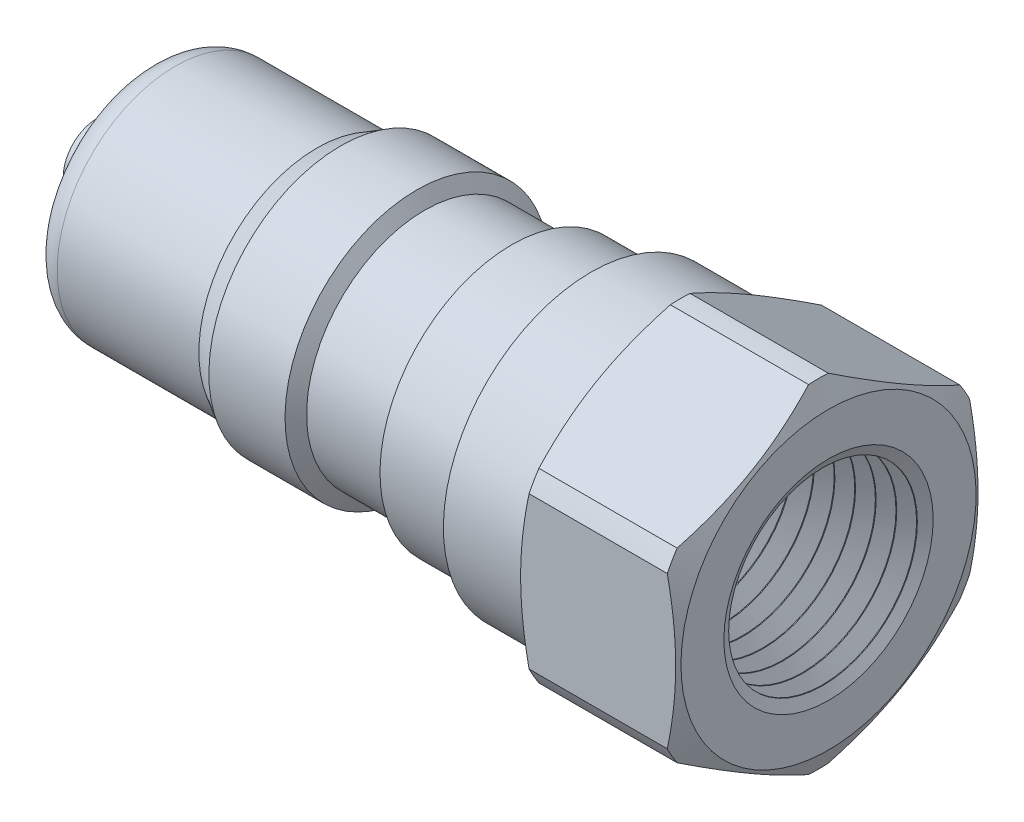
SolidWorks part; units mm, degrees
ref_plane "Front" through (0, 0, 0) normal (0, 0, 1) x (1, 0, 0)
ref_plane "Top" through (0, 0, 0) normal (0, 1, 0) x (1, 0, 0)
ref_plane "Right" through (0, 0, 0) normal (1, 0, 0) x (0, 0, -1)
sketch "Sketch1" plane through (0, 0, 0) normal (0, 0, 1) x (1, 0, 0)
  line L0 (0, 0) -> (0, 4.2025)
  line L1 (0, 4.2025) -> (0.4447, 5.0315) construction
  line L2 (0.4447, 5.0315) -> (0.9403, 4.2319) construction
  line L3 (0.9403, 4.2319) -> (1.385, 5.0609) construction
  line L4 (1.385, 5.0609) -> (1.8806, 4.2613) construction
  line L5 (0.9572, 4.2635) -> (1.368, 5.0293)
  line L6 (1.368, 5.0293) -> (1.4039, 5.0304)
  line L7 (1.4039, 5.0304) -> (1.8617, 4.2918)
  line L8 (1.8617, 4.2918) -> (1.8975, 4.2929)
  line L9 (0, 4.2025) -> (1.8806, 4.2613) construction
  line L10 (0.4447, 5.0315) -> (1.385, 5.0609) construction
  line L11 (0.2223, 4.617) -> (1.6328, 4.6611) construction
  line L12 (0, 0) -> (-4.2025, 0) construction
  line L13 (1.8975, 4.2929) -> (2.3083, 5.0587)
  line L14 (0.017, 4.2342) -> (0.4277, 4.9999)
  line L15 (0.4277, 4.9999) -> (0.4636, 5.0011)
  line L16 (0.4636, 5.0011) -> (0.9214, 4.2624)
  line L17 (0.9214, 4.2624) -> (0.9572, 4.2635)
  line L18 (0.2223, 4.617) -> (0, 4.6101) construction
  line L19 (0, 4.6101) -> (0, 4.2025) construction
  line L20 (0.2223, -4.617) -> (0, -4.6101) construction
  line L21 (0.017, 4.2342) -> (0, 4.2025)
  line L22 (2.3083, 5.0587) -> (2.3441, 5.0598)
  line L23 (2.3441, 5.0598) -> (2.802, 4.3212)
  line L24 (2.802, 4.3212) -> (2.8378, 4.3223)
  line L25 (2.8378, 4.3223) -> (3.2486, 5.0881)
  line L26 (3.2486, 5.0881) -> (3.2844, 5.0892)
  line L27 (3.2844, 5.0892) -> (3.7422, 4.3506)
  line L28 (3.7422, 4.3506) -> (3.7781, 4.3517)
  line L29 (3.7781, 4.3517) -> (4.1889, 5.1175)
  line L30 (4.1889, 5.1175) -> (4.2247, 5.1186)
  line L31 (4.2247, 5.1186) -> (4.6825, 4.38)
  line L32 (4.6825, 4.38) -> (4.7184, 4.3811)
  line L33 (4.7184, 4.3811) -> (5.1291, 5.1469)
  line L34 (5.1291, 5.1469) -> (5.165, 5.148)
  line L35 (5.165, 5.148) -> (5.6228, 4.4093)
  line L36 (5.6228, 4.4093) -> (5.6586, 4.4105)
  line L37 (5.6586, 4.4105) -> (6.0694, 5.1763)
  line L38 (6.0694, 5.1763) -> (6.1053, 5.1774)
  line L39 (6.1053, 5.1774) -> (6.5631, 4.4387)
  line L40 (6.5631, 4.4387) -> (6.5989, 4.4398)
  line L41 (6.5989, 4.4398) -> (7.0097, 5.2056)
  line L42 (7.0097, 5.2056) -> (7.0456, 5.2068)
  line L43 (7.0456, 5.2068) -> (7.5034, 4.4681)
  line L44 (7.5034, 4.4681) -> (7.5392, 4.4692)
  line L45 (7.5392, 4.4692) -> (7.95, 5.235)
  line L46 (7.95, 5.235) -> (7.9858, 5.2361)
  line L47 (7.9858, 5.2361) -> (8.4436, 4.4975)
  line L48 (8.4436, 4.4975) -> (8.4795, 4.4986)
  line L49 (8.4795, 4.4986) -> (8.8903, 5.2644)
  line L50 (8.8903, 5.2644) -> (8.9261, 5.2655)
  line L51 (8.9261, 5.2655) -> (9.3839, 4.5269)
  line L52 (9.3839, 4.5269) -> (9.4198, 4.528)
  line L53 (9.4198, 4.528) -> (9.8306, 5.2938)
  line L54 (9.8306, 5.2938) -> (9.8664, 5.2949)
  line L55 (9.8664, 5.2949) -> (10.3242, 4.5563)
  line L56 (10.3242, 4.5563) -> (10.3601, 4.5574)
  line L57 (10.3601, 4.5574) -> (10.7708, 5.3232)
  line L58 (10.7708, 5.3232) -> (10.8067, 5.3243)
  line L59 (10.8067, 5.3243) -> (11.2645, 4.5857)
  line L60 (11.2645, 4.5857) -> (11.3003, 4.5868)
  line L61 (0, 0) -> (-25.146, 0) construction
  line L62 (0, 3.4163) -> (0, -3.4163) construction
  line L63 (13.1809, 4.6455) -> (13.1809, 0)
  line L64 (-4.318, 0) -> (0, 0) construction
  line L73 (0, 0) -> (13.1809, 0)
  line L75 (0.4457, 5.0005) -> (0.4447, 5.0315) construction
  line L76 (1.6328, 4.6611) -> (6.7056, 4.8197) construction
  line L77 (6.7056, 4.8197) -> (6.7056, 0) construction
  line L78 (6.7056, 4.8197) -> (6.858, 4.8244) construction
  line L79 (6.858, 4.8244) -> (6.858, 0) construction
  line L80 (6.858, 4.8244) -> (6.858, 5.1435) construction
  line L81 (6.858, 5.1435) -> (11.3003, 5.1435) construction
  line L82 (11.3003, 5.1435) -> (11.3003, 4.5868) construction
  line L84 (6.7056, 4.4432) -> (6.858, 4.4479) construction
  line L87 (6.858, 4.2025) -> (0, 4.2025) construction
  line L89 (11.3003, 4.5868) -> (11.7111, 5.3526)
  line L90 (11.7111, 5.3526) -> (11.747, 5.3537)
  line L91 (11.747, 5.3537) -> (12.2048, 4.615)
  line L92 (12.2048, 4.615) -> (12.2406, 4.6162)
  line L93 (12.2406, 4.6162) -> (12.6514, 5.382)
  line L94 (12.6514, 5.382) -> (12.6872, 5.3831)
  line L95 (12.6872, 5.3831) -> (13.145, 4.6444)
  line L96 (13.145, 4.6444) -> (13.1809, 4.6455)
  point P75 (-4.318, 0)
  point P79 (-0.5927, 0)
  dimension "D1" = 60
  dimension "E0" = 9.2202
  dimension "Thread Pitch" = 0.9407
  dimension "D4" = 3.58
  dimension "D2" = 0.031
  dimension "D3" = 0.0359
  dimension "L2 Thread Engagement" = 6.7056
  dimension "L4 Thread Length" = 6.858
  dimension "Pipe OD" = 10.287
  dimension "ID" = 6.8326
  dimension "Length" = 32.004
  dimension "Plug End" = 20.828
  dimension "D5" = 3.7253
  dimension "D6" = 11.176
revolve "Revolve1" add sketch "Sketch1" angle 360 about L12
sketch "Sketch12" plane through (0, 0, 0) normal (0, 0, 1) x (1, 0, 0)
  line L1 (6.858, 0) -> (35.3453, 0)
  line L2 (6.858, 0) -> (6.858, 19.5295)
  line L3 (6.858, 19.5295) -> (35.3453, 19.5295)
  line L4 (35.3453, 0) -> (35.3453, 19.5295)
revolve "Cut-Revolve6" cut sketch "Sketch12" angle 360 about L61
sketch "Sketch8" plane through (6.858, 0, 0) normal (1, 0, 0) x (0, 0, -1)
  line L1 (0, 8.2122) -> (-7.112, 4.1061)
  line L2 (-7.112, 4.1061) -> (-7.112, -4.1061)
  line L3 (-7.112, -4.1061) -> (0, -8.2122)
  line L4 (0, -8.2122) -> (7.112, -4.1061)
  line L5 (7.112, -4.1061) -> (7.112, 4.1061)
  line L6 (7.112, 4.1061) -> (0, 8.2122)
  circle A0 centre (0, 0) radius 7.112 construction
  dimension "Hex" = 14.224
extrude "Extrude1" add sketch "Sketch8" against normal up to vertex (7.4507 mm away) separate body up to point (-0.5927, 0, 0)
sketch "Sketch9" plane through (0, 0, 0) normal (0, 0, 1) x (1, 0, 0)
  line L0 (-0.5927, 6.9422) -> (-0.1189, 7.9582)
  line L1 (-0.5927, 4.1061) -> (-0.5927, 8.2122) construction
  line L2 (-0.1189, 7.9582) -> (6.3842, 7.9582)
  line L3 (6.3842, 7.9582) -> (6.858, 6.9422)
  line L4 (6.858, 4.1061) -> (6.858, 8.2122) construction
  line L5 (6.858, 6.9422) -> (6.858, 8.2122)
  line L6 (6.858, 8.2122) -> (-0.5927, 8.2122)
  line L7 (-0.5927, 8.2122) -> (-0.5927, 6.9422)
  dimension "D1" = 25
  dimension "D2" = 0.254
  dimension "D3" = 1.27
  dimension "D4" = 25
revolve "Cut-Revolve4" cut sketch "Sketch9" angle 360 about L61
sketch "Sketch10" plane through (0, 0, 0) normal (0, 0, 1) x (1, 0, 0)
  line L0 (-0.5927, 0) -> (-25.146, 0)
  line L1 (-25.146, 0) -> (-25.146, -5.5562)
  line L2 (-25.146, -5.5562) -> (-17.2085, -5.5562)
  line L3 (-17.2085, -5.5562) -> (-16.0944, -6.1995)
  line L4 (-16.0944, -6.1995) -> (-12.5114, -6.1995)
  line L5 (-12.5114, -6.1995) -> (-12.14, -5.5563)
  line L6 (-12.14, -5.5563) -> (-8.4147, -5.5562)
  line L7 (-8.4147, -5.5562) -> (-8.0433, -6.1995)
  line L8 (-8.0433, -6.1995) -> (-4.318, -6.1995)
  line L9 (-0.5927, -6.9422) -> (-0.5927, 6.9422) construction
  line L10 (-0.5927, -6.9422) -> (-0.5927, 0)
  line L11 (-25.146, -5.5562) -> (-25.146, 5.5562) construction
  line L12 (-4.318, -6.1995) -> (-4.318, -6.9422)
  line L13 (-4.318, -6.9422) -> (-0.5927, -6.9422)
  dimension "D1" = 60
  dimension "A" = 11.1125
  dimension "B" = 7.9375
  dimension "D2" = 30
revolve "Revolve3" add sketch "Sketch10" angle 360 about L12
fillet "Fillet1" radius 1.27 1 edges at (-25.146, 5.5562, 0)
combine bodies "Combine3" operation type subtract bodies to subtract 128
sketch "Sketch13" plane through (0, 0, 0) normal (0, 0, 1) x (1, 0, 0)
  line L0 (-25.146, 2.3464) -> (-26.7462, 1.6002) construction
  line L1 (-26.7462, 1.6002) -> (-26.7462, 0) construction
  line L2 (-25.146, -5.5562) -> (-25.146, 5.5562) construction
  line L3 (-26.7462, 1.6002) -> (-27.5463, 1.6002) construction
  line L4 (-27.5463, 1.6002) -> (-27.5463, 0) construction
  line L5 (-27.5463, 0) -> (-25.146, 0) construction
  line L6 (-25.146, 0) -> (-25.146, 2.3464)
  line L7 (-26.7462, 0) -> (-25.9461, 0) construction
  line L8 (-25.9461, 0) -> (-25.146, 0) construction
  line L9 (-26.7462, 0) -> (-27.5463, 0) construction
  line L10 (-26.7462, 1.6002) -> (-26.7462, 0.8001) construction
  line L11 (-25.146, 2.3464) -> (-26.7462, 1.6002)
  line L12 (-26.7462, 1.6002) -> (-27.5463, 1.6002)
  line L13 (-27.5463, 1.6002) -> (-27.5463, 0)
  line L14 (-27.5463, 0) -> (-25.146, 0)
  dimension "D2" = 2.4003
  dimension "D4" = 65
revolve "Revolve4" add sketch "Sketch13" angle 360 about L61
equation "\"D2@Sketch1\"=\"Thread Pitch@Sketch1\"*.033"
equation "\"D2@Sketch13\" = \"Length@Sketch1\"*.075"
equation "\"D5@Sketch1\" = \"D6@Sketch1\"/3"
